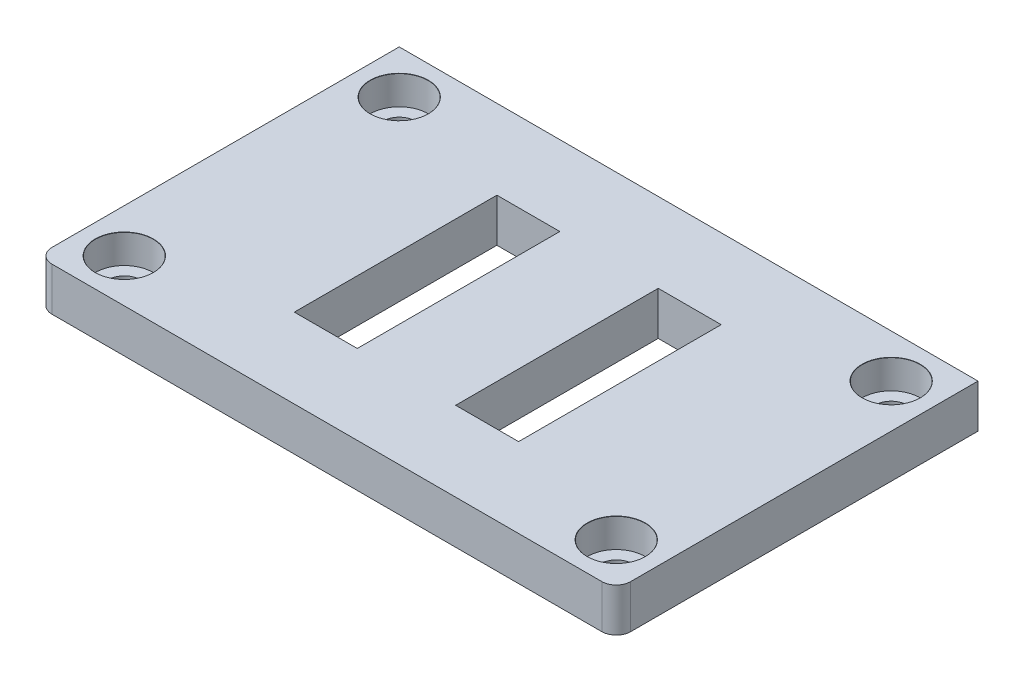
SolidWorks part; units mm, degrees
ref_plane "Front Plane" through (0, 0, 0) normal (0, 0, 1) x (1, 0, 0)
ref_plane "Top Plane" through (0, 0, 0) normal (0, 1, 0) x (1, 0, 0)
ref_plane "Right Plane" through (0, 0, 0) normal (1, 0, 0) x (0, 0, -1)
sketch "Sketch2" plane through (0, 0, 0) normal (0, 1, 0) x (1, 0, 0)
  line L1 (-20, 25) -> (20, 25)
  line L2 (-20, 25) -> (-20, -25)
  line L3 (-20, -25) -> (20, -25)
  line L4 (20, 25) -> (20, -25)
  line L5 (-20, 25) -> (20, -25) construction
  line L6 (-20, -25) -> (20, 25) construction
  line L12 (4.5, -14) -> (4.5, 14)
  line L16 (13.2, 14) -> (4.5, 14)
  line L17 (4.5, -14) -> (13.2, -14)
  line L20 (13.2, 14) -> (13.2, -14)
  point P0 (0, 0)
  point P17 (4.5, 0)
  dimension "D1" = 50
  dimension "D2" = 40
  dimension "D3" = 8.7
  dimension "D4" = 24.5
  dimension "D5" = 28
extrude "Boss-Extrude1" add sketch "Sketch2" along normal blind 6
hole_wizard "CBORE for M4 SHCS2" positions "Sketch3" profile "Sketch4" counterbore size "M4" standard "ANSI Metric" end condition through all
sketch "Sketch3" plane through (0, 6, 0) normal (0, 1, 0) x (1, 0, 0)
  line L8 (-20, 25) -> (-20, -25) construction
  line L10 (-14, -19) -> (-14, 19) construction
  line L12 (20, 25) -> (-20, 25) construction
  point P6 (-14, -19)
  point P34 (-14, 19)
  point P38 (-20, 0)
  point P39 (-14, 0)
  dimension "D1" = 6
  dimension "D2" = 6
sketch "Sketch4" plane through (-14, 6, 19) normal (1, 0, 0) x (0, 0, 1)
  line L0 (0, 0) -> (0, 6)
  line L1 (0, 6) -> (2.25, 6)
  line L3 (2.25, 6) -> (2.25, 4)
  line L4 (4, 4) -> (2.25, 4)
  line L5 (4, 4) -> (4, 0.025)
  line L6 (4, 0.025) -> (4.025, 0)
  line L7 (4.025, 0) -> (0, 0)
  line L8 (-4, 0.025) -> (-4.025, 0) construction
  line L11 (0, -6.35) -> (0, 107.95) construction
  dimension "Thru Hole Dia." = 4.5
  dimension "Thru Hole Depth" = 6
  dimension "C'Bore Dia." = 8
  dimension "C'Bore Depth" = 4
  dimension "Near C'Sink Dia." = 8.05
  dimension "Near C'Sink Angle" = 90
ref_plane "Plane1" through (20, 0, 0) normal (1, 0, 0) x (0, 0, -1)
mirror "Mirror1" about plane through (20, 0, 0) normal (1, 0, 0) of "CBORE for M4 SHCS2", "Boss-Extrude1"
fillet "Fillet1" radius 2 2 edges at (60, 3, 25) (-20, 3, 25)
